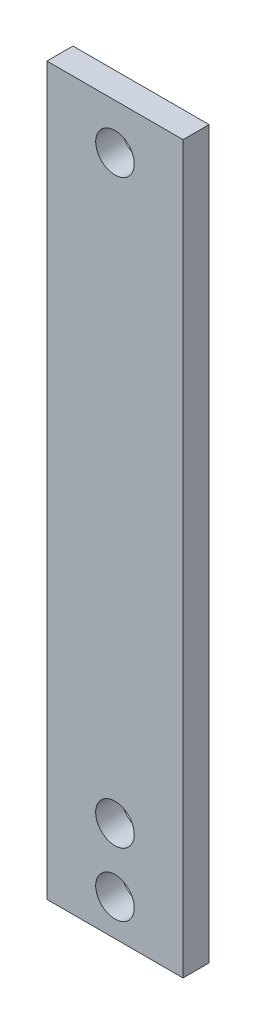
SolidWorks part; units mm, degrees
ref_plane "Front Plane" through (0, 0, 0) normal (0, 0, 1) x (1, 0, 0)
ref_plane "Top Plane" through (0, 0, 0) normal (0, 1, 0) x (1, 0, 0)
ref_plane "Right Plane" through (0, 0, 0) normal (1, 0, 0) x (0, 0, -1)
sketch "Sketch1" plane through (0, 0, 0) normal (0, 0, 1) x (1, 0, 0)
  line L0 (0, -40) -> (0, 40) construction
  line L1 (-7.5, 40) -> (7.5, 40)
  line L2 (-7.5, 40) -> (-7.5, -40)
  line L3 (-7.5, -40) -> (7.5, -40)
  line L4 (7.5, 40) -> (7.5, -40)
  line L5 (-7.5, 40) -> (7.5, -40) construction
  line L6 (-7.5, -40) -> (7.5, 40) construction
  line L7 (-7.5, -25) -> (7.5, -25) construction
  circle A0 centre (0, -36) radius 2.125
  circle A1 centre (0, -29) radius 2.125
  circle A2 centre (0, 35) radius 2.125
  point P0 (0, 0)
  point P9 (0, 0)
  dimension "D3" = 4.25
  dimension "D7" = 4.25
  dimension "D1" = 15
  dimension "D2" = 80
  dimension "D4" = 4
  dimension "D5" = 15
  dimension "D6" = 4
  dimension "D8" = 5
extrude "Boss-Extrude1" add sketch "Sketch1" along normal blind 2.87
